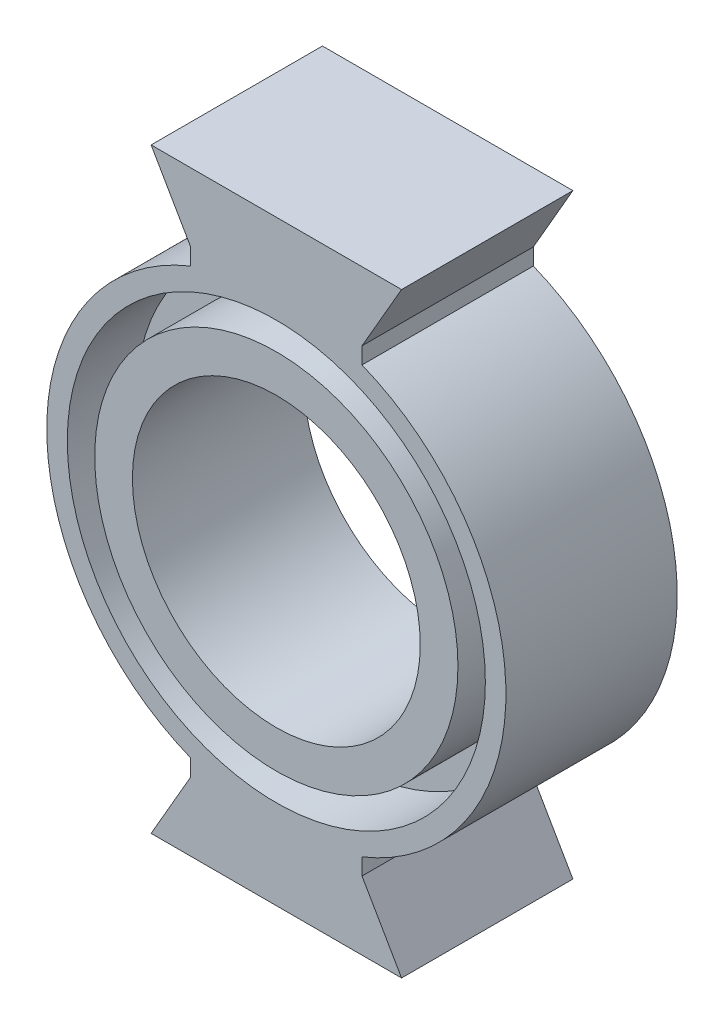
SolidWorks part; units mm, degrees
ref_plane "Front" through (0, 0, 0) normal (0, 0, 1) x (1, 0, 0)
ref_plane "Top" through (0, 0, 0) normal (0, 1, 0) x (1, 0, 0)
ref_plane "Right" through (0, 0, 0) normal (1, 0, 0) x (0, 0, -1)
sketch "Sketch1" plane through (0, 0, 0) normal (0, 0, 1) x (1, 0, 0)
  circle A0 centre (0, 0) radius 5.334
  circle A1 centre (0, 0) radius 8.509
  dimension "D1" = 10.668
  dimension "D2" = 17.018
extrude "Boss-Extrude1" add sketch "Sketch1" along normal blind 6.35
sketch "Sketch2" plane through (0, 0, 6.35) normal (0, 0, 1) x (1, 0, 0)
  circle A0 centre (0, 0) radius 6.731
  circle A1 centre (0, 0) radius 7.747
  dimension "D1" = 13.462
  dimension "D2" = 15.494
extrude "Cut-Extrude1" cut sketch "Sketch2" against normal blind 2.54
sketch "Sketch3" plane through (0, 0, 0) normal (0, 0, 1) x (1, 0, 0)
  line L4 (-3.175, 7.8945) -> (-3.175, 8.509)
  line L5 (3.175, 7.8945) -> (3.175, 8.509)
  line L6 (3.175, 8.509) -> (4.6415, 11.049)
  line L7 (4.6415, 11.049) -> (-4.6415, 11.049)
  line L8 (-4.6415, 11.049) -> (-3.175, 8.509)
  line L9 (-3.175, 8.509) -> (3.175, 8.509) construction
  circle A2 centre (0, 0) radius 8.509 construction
  arc A3 (-3.175, 7.8945) -> (3.175, 7.8945) centre (0, 0) cw
  point P10 (0, 8.509)
  dimension "D1" = 17.018
  dimension "D2" = 6.35
  dimension "D3" = 60
  dimension "D4" = 60
  dimension "D5" = 2.54
extrude "Boss-Extrude2" add sketch "Sketch3" along normal up to surface (6.35 mm away) up to face at (7.747, 0, 6.35)
mirror "Mirror1" about plane through (0, 0, 0) normal (0, 1, 0) of "Boss-Extrude2"
ref_plane "Plane1" through (0, 0, 3.175) normal (0, 0, -1) x (-1, 0, 0)
mirror "Mirror2" about plane through (0, 0, 3.175) normal (0, 0, -1) of "Cut-Extrude1"
